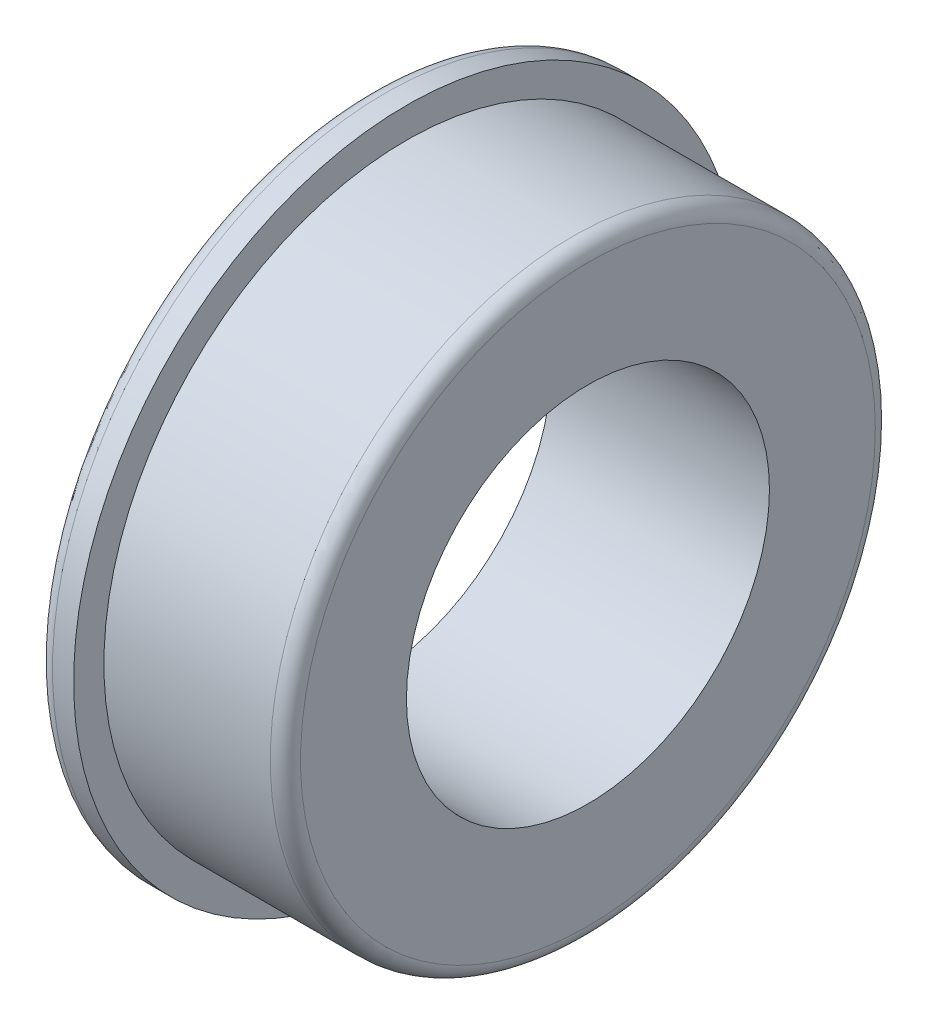
SolidWorks part; units mm, degrees
ref_plane "Front Plane" through (0, 0, 0) normal (0, 0, 1) x (1, 0, 0)
ref_plane "Top Plane" through (0, 0, 0) normal (0, 1, 0) x (1, 0, 0)
ref_plane "Right Plane" through (0, 0, 0) normal (1, 0, 0) x (0, 0, -1)
sketch "Sketch1" plane through (0, 0, 0) normal (1, 0, 0) x (0, 0, -1)
  circle A0 centre (0, 0) radius 5.5
  dimension "D1" = 11
extrude "Boss-Extrude1" add sketch "Sketch1" along normal blind 0.6
sketch "Sketch2" plane through (0.6, 0, 0) normal (1, 0, 0) x (0, 0, -1)
  circle A0 centre (0, 0) radius 5
  dimension "D1" = 10
extrude "Boss-Extrude2" add sketch "Sketch2" along normal blind 3
sketch "Sketch3" plane through (3.6, 0, 0) normal (1, 0, 0) x (0, 0, -1)
  circle A0 centre (0, 0) radius 3
  dimension "D1" = 6
extrude "Cut-Extrude1" cut sketch "Sketch3" against normal through all
sketch "Sketch4" plane through (0, 0, 0) normal (-1, 0, 0) x (0, 0, 1)
  circle A0 centre (0, 0) radius 4.75
  circle A1 centre (0, 0) radius 4.375
  dimension "D1" = 9.5
  dimension "D2" = 8.75
extrude "Cut-Extrude2" cut sketch "Sketch4" against normal blind 0.25
fillet "Fillet1" radius 0.25 1 edges at (0, 0, -5.5)
fillet "Fillet2" radius 0.25 1 edges at (3.6, 0, -5)
